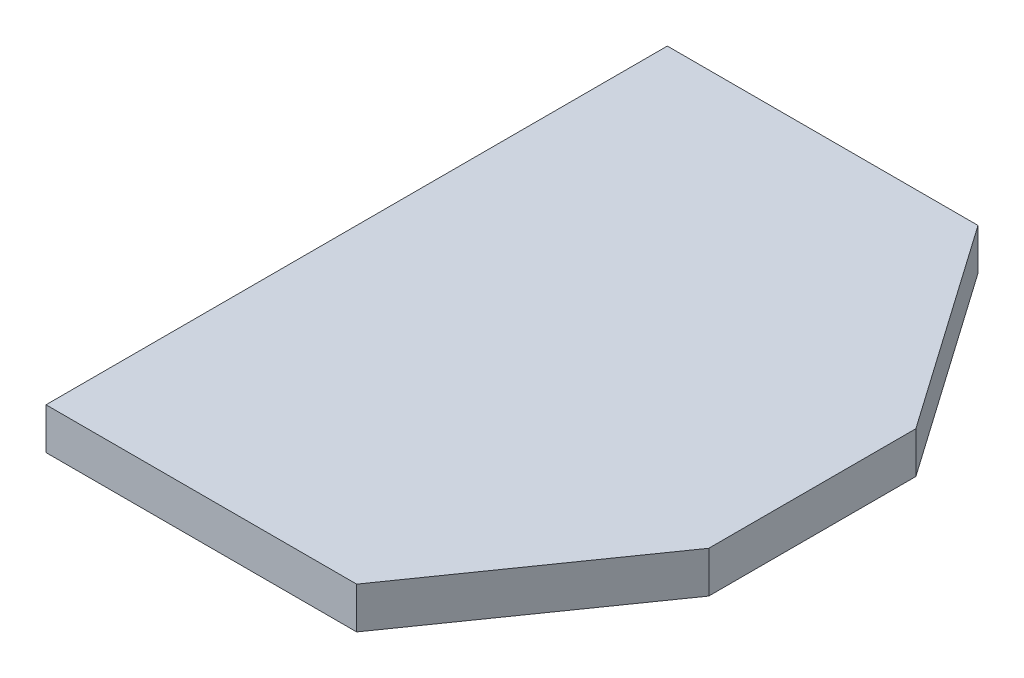
SolidWorks part; units mm, degrees
material "Nylon PA 12"
ref_plane "Front Plane" through (0, 0, 0) normal (0, 0, 1) x (1, 0, 0)
ref_plane "Top Plane" through (0, 0, 0) normal (0, 1, 0) x (1, 0, 0)
ref_plane "Right Plane" through (0, 0, 0) normal (1, 0, 0) x (0, 0, -1)
sketch "Sketch1" plane through (0, 0, 0) normal (0, 1, 0) x (1, 0, 0)
  line L1 (29, -25) -> (104, -25)
  line L2 (29, -25) -> (29, 125)
  line L3 (29, 125) -> (104, 125)
  line L5 (104, 125) -> (139, 75)
  line L6 (139, 25) -> (139, 75)
  line L10 (229.0766, 50) -> (29, 50) construction
  line L11 (104, -25) -> (139, 25)
  point P0 (0, 0)
  point P6 (139, 50)
  point P7 (139, 81.5729)
  dimension "D1" = 75
  dimension "D2" = 50
  dimension "D6" = 150
  dimension "D8" = 110
extrude "Boss-Extrude1" add sketch "Sketch1" along normal mid plane 10
sketch "Sketch2" [suppressed] plane through (0, 0, -125) normal (0, 0, -1) x (-1, 0, 0)
  line L0 (-75, -5) -> (75, -5)
  line L1 (75, -5) -> (75, -35)
  line L2 (75, -35) -> (-75, -35)
  line L3 (-75, -35) -> (-75, -5)
  dimension "D1" = 30
